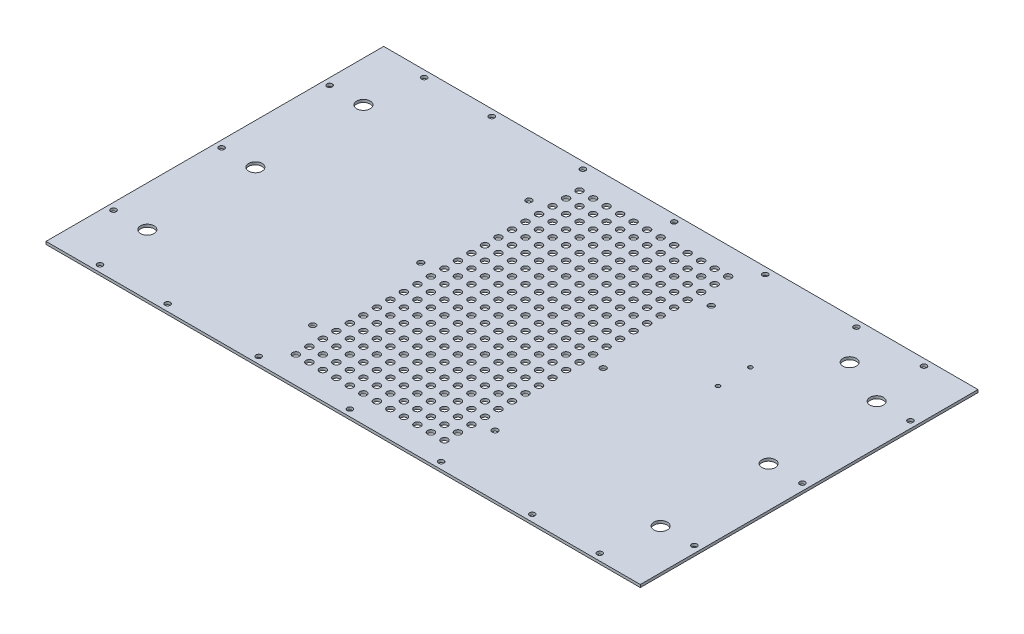
SolidWorks part; units mm, degrees
ref_plane "Alzado" through (0, 0, 0) normal (0, 0, 1) x (1, 0, 0)
ref_plane "Planta" through (0, 0, 0) normal (0, 1, 0) x (1, 0, 0)
ref_plane "Vista lateral" through (0, 0, 0) normal (1, 0, 0) x (0, 0, -1)
sketch "Croquis1" plane through (0, 0, 0) normal (0, 1, 0) x (1, 0, 0)
  line L8 (-100, 125) -> (-100, -125) construction
  line L9 (100, 125) -> (100, -125) construction
  line L13 (160, 125) -> (160, -125) construction
  line L16 (-220, 125) -> (-100, 125)
  line L17 (0, 125) -> (0, -125) construction
  line L20 (-100, 125) -> (100, 125)
  line L22 (-220, 0) -> (220, 0) construction
  line L24 (100, 125) -> (220, 125)
  line L26 (-60, 110) -> (-60, -110)
  line L28 (-220, -125) -> (-100, -125)
  line L31 (-100, -125) -> (100, -125)
  line L34 (100, -125) -> (220, -125)
  line L38 (-220, 125) -> (-220, -125)
  line L40 (-100, 125) -> (-100, -125)
  line L41 (100, 125) -> (100, -125)
  line L42 (-77.5, 102.5) -> (-77.5, 57.5) construction
  line L43 (220, 125) -> (220, -125)
  line L45 (-60, -110) -> (60, -110)
  line L46 (60, -110) -> (60, 110)
  line L47 (60, 110) -> (-60, 110)
  line L48 (-77.5, 57.5) -> (77.5, 57.5) construction
  line L49 (77.5, 57.5) -> (77.5, 102.5) construction
  line L50 (77.5, 102.5) -> (-77.5, 102.5) construction
  line L51 (-77.5, 22.5) -> (-77.5, -22.5) construction
  line L52 (-77.5, -22.5) -> (77.5, -22.5) construction
  line L53 (77.5, -22.5) -> (77.5, 22.5) construction
  line L54 (77.5, 22.5) -> (-77.5, 22.5) construction
  line L55 (-77.5, -57.5) -> (-77.5, -102.5) construction
  line L56 (-77.5, -102.5) -> (77.5, -102.5) construction
  line L57 (77.5, -102.5) -> (77.5, -57.5) construction
  line L58 (77.5, -57.5) -> (-77.5, -57.5) construction
  line L59 (-210, 115) -> (-210, -115) construction
  line L60 (-210, -115) -> (210, -115) construction
  line L61 (210, -115) -> (210, 115) construction
  line L62 (210, 115) -> (-210, 115) construction
  line L63 (-190, 125) -> (-190, -125) construction
  line L64 (190, 125) -> (190, -125) construction
  circle A0 centre (-190, 80) radius 5
  circle A1 centre (-190, 0) radius 5
  circle A2 centre (-190, -80) radius 5
  circle A3 centre (190, -80) radius 5
  circle A4 centre (190, 0) radius 5
  circle A5 centre (190, 80) radius 5
  circle A8 centre (-67.5, 80) radius 2.175
  circle A10 centre (-67.5, 0) radius 2.175
  circle A11 centre (-67.5, -80) radius 2.175
  circle A12 centre (67.5, -80) radius 2.175
  circle A13 centre (67.5, 0) radius 2.175
  circle A14 centre (67.5, 80) radius 2.175
  circle A15 centre (155, 95) radius 5
  point P8 (0, 125)
  point P44 (-220, 0)
  point P45 (-77.5, 80)
  point P46 (0, 102.5)
  point P47 (0, 110)
  dimension "D10" = 10
  dimension "D6" = 15
  dimension "D13" = 22.5
  dimension "D22" = 4.35
  dimension "D15" = 10
  dimension "D17" = 5
  dimension "D3" = 200
  dimension "D4" = 120
  dimension "D5" = 250
  dimension "D7" = 15
  dimension "D8" = 80
  dimension "D9" = 80
  dimension "D11" = 40
  dimension "D12" = 40
  dimension "D14" = 250
  dimension "D16" = 120
  dimension "D18" = 155
  dimension "D19" = 45
  dimension "D20" = 7.5
  dimension "D21" = 440
  dimension "D24" = 10
  dimension "D25" = 10
  dimension "D26" = 10
  dimension "D27" = 10
  dimension "D28" = 10
  dimension "D29" = 10
  dimension "D30" = 30
  dimension "D31" = 30
  dimension "D32" = 20
  dimension "D23" = 3
extrude "Saliente-Extruir1" add sketch "Croquis1" along normal blind 2 contours L40 L16 L38 L28 A2 A1 A0 | L41 L20 L40 L31 L47 L46 L45 L26 | L43 L24 L41 L34 A4 A3 A5
sketch "Croquis4" plane through (0, 2, 0) normal (0, 1, 0) x (1, 0, 0)
  line L0 (-60, 110) -> (-60, -110)
  line L1 (-60, -110) -> (60, -110)
  line L2 (60, -110) -> (60, 110)
  line L3 (60, 110) -> (-60, 110)
  circle A0 centre (-55, 105) radius 2.5
  circle A1 centre (-45, 105) radius 2.5
  circle A2 centre (-35, 105) radius 2.5
  circle A3 centre (-25, 105) radius 2.5
  circle A4 centre (-15, 105) radius 2.5
  circle A5 centre (-5, 105) radius 2.5
  circle A6 centre (5, 105) radius 2.5
  circle A7 centre (15, 105) radius 2.5
  circle A8 centre (25, 105) radius 2.5
  circle A9 centre (35, 105) radius 2.5
  circle A10 centre (45, 105) radius 2.5
  circle A12 centre (-45, 95) radius 2.5
  circle A13 centre (-35, 95) radius 2.5
  circle A14 centre (-25, 95) radius 2.5
  circle A15 centre (-15, 95) radius 2.5
  circle A16 centre (-5, 95) radius 2.5
  circle A17 centre (5, 95) radius 2.5
  circle A18 centre (15, 95) radius 2.5
  circle A19 centre (25, 95) radius 2.5
  circle A20 centre (35, 95) radius 2.5
  circle A21 centre (45, 95) radius 2.5
  circle A23 centre (-45, 85) radius 2.5
  circle A24 centre (-35, 85) radius 2.5
  circle A25 centre (-25, 85) radius 2.5
  circle A26 centre (-15, 85) radius 2.5
  circle A27 centre (-5, 85) radius 2.5
  circle A28 centre (5, 85) radius 2.5
  circle A29 centre (15, 85) radius 2.5
  circle A30 centre (25, 85) radius 2.5
  circle A31 centre (35, 85) radius 2.5
  circle A32 centre (45, 85) radius 2.5
  circle A34 centre (-45, 75) radius 2.5
  circle A35 centre (-35, 75) radius 2.5
  circle A36 centre (-25, 75) radius 2.5
  circle A37 centre (-15, 75) radius 2.5
  circle A38 centre (-5, 75) radius 2.5
  circle A39 centre (5, 75) radius 2.5
  circle A40 centre (15, 75) radius 2.5
  circle A41 centre (25, 75) radius 2.5
  circle A42 centre (35, 75) radius 2.5
  circle A43 centre (45, 75) radius 2.5
  circle A45 centre (-45, 65) radius 2.5
  circle A46 centre (-35, 65) radius 2.5
  circle A47 centre (-25, 65) radius 2.5
  circle A48 centre (-15, 65) radius 2.5
  circle A49 centre (-5, 65) radius 2.5
  circle A50 centre (5, 65) radius 2.5
  circle A51 centre (15, 65) radius 2.5
  circle A52 centre (25, 65) radius 2.5
  circle A53 centre (35, 65) radius 2.5
  circle A54 centre (45, 65) radius 2.5
  circle A56 centre (-45, 55) radius 2.5
  circle A57 centre (-35, 55) radius 2.5
  circle A58 centre (-25, 55) radius 2.5
  circle A59 centre (-15, 55) radius 2.5
  circle A60 centre (-5, 55) radius 2.5
  circle A61 centre (5, 55) radius 2.5
  circle A62 centre (15, 55) radius 2.5
  circle A63 centre (25, 55) radius 2.5
  circle A64 centre (35, 55) radius 2.5
  circle A65 centre (45, 55) radius 2.5
  circle A67 centre (-45, 45) radius 2.5
  circle A68 centre (-35, 45) radius 2.5
  circle A69 centre (-25, 45) radius 2.5
  circle A70 centre (-15, 45) radius 2.5
  circle A71 centre (-5, 45) radius 2.5
  circle A72 centre (5, 45) radius 2.5
  circle A73 centre (15, 45) radius 2.5
  circle A74 centre (25, 45) radius 2.5
  circle A75 centre (35, 45) radius 2.5
  circle A76 centre (45, 45) radius 2.5
  circle A78 centre (-45, 35) radius 2.5
  circle A79 centre (-35, 35) radius 2.5
  circle A80 centre (-25, 35) radius 2.5
  circle A81 centre (-15, 35) radius 2.5
  circle A82 centre (-5, 35) radius 2.5
  circle A83 centre (5, 35) radius 2.5
  circle A84 centre (15, 35) radius 2.5
  circle A85 centre (25, 35) radius 2.5
  circle A86 centre (35, 35) radius 2.5
  circle A87 centre (45, 35) radius 2.5
  circle A89 centre (-45, 25) radius 2.5
  circle A90 centre (-35, 25) radius 2.5
  circle A91 centre (-25, 25) radius 2.5
  circle A92 centre (-15, 25) radius 2.5
  circle A93 centre (-5, 25) radius 2.5
  circle A94 centre (5, 25) radius 2.5
  circle A95 centre (15, 25) radius 2.5
  circle A96 centre (25, 25) radius 2.5
  circle A97 centre (35, 25) radius 2.5
  circle A98 centre (45, 25) radius 2.5
  circle A100 centre (-45, 15) radius 2.5
  circle A101 centre (-35, 15) radius 2.5
  circle A102 centre (-25, 15) radius 2.5
  circle A103 centre (-15, 15) radius 2.5
  circle A104 centre (-5, 15) radius 2.5
  circle A105 centre (5, 15) radius 2.5
  circle A106 centre (15, 15) radius 2.5
  circle A107 centre (25, 15) radius 2.5
  circle A108 centre (35, 15) radius 2.5
  circle A109 centre (45, 15) radius 2.5
  circle A111 centre (-45, 5) radius 2.5
  circle A112 centre (-35, 5) radius 2.5
  circle A113 centre (-25, 5) radius 2.5
  circle A114 centre (-15, 5) radius 2.5
  circle A115 centre (-5, 5) radius 2.5
  circle A116 centre (5, 5) radius 2.5
  circle A117 centre (15, 5) radius 2.5
  circle A118 centre (25, 5) radius 2.5
  circle A119 centre (35, 5) radius 2.5
  circle A120 centre (45, 5) radius 2.5
  circle A122 centre (-45, -5) radius 2.5
  circle A123 centre (-35, -5) radius 2.5
  circle A124 centre (-25, -5) radius 2.5
  circle A125 centre (-15, -5) radius 2.5
  circle A126 centre (-5, -5) radius 2.5
  circle A127 centre (5, -5) radius 2.5
  circle A128 centre (15, -5) radius 2.5
  circle A129 centre (25, -5) radius 2.5
  circle A130 centre (35, -5) radius 2.5
  circle A131 centre (45, -5) radius 2.5
  circle A133 centre (-45, -15) radius 2.5
  circle A134 centre (-35, -15) radius 2.5
  circle A135 centre (-25, -15) radius 2.5
  circle A136 centre (-15, -15) radius 2.5
  circle A137 centre (-5, -15) radius 2.5
  circle A138 centre (5, -15) radius 2.5
  circle A139 centre (15, -15) radius 2.5
  circle A140 centre (25, -15) radius 2.5
  circle A141 centre (35, -15) radius 2.5
  circle A142 centre (45, -15) radius 2.5
  circle A144 centre (-45, -25) radius 2.5
  circle A145 centre (-35, -25) radius 2.5
  circle A146 centre (-25, -25) radius 2.5
  circle A147 centre (-15, -25) radius 2.5
  circle A148 centre (-5, -25) radius 2.5
  circle A149 centre (5, -25) radius 2.5
  circle A150 centre (15, -25) radius 2.5
  circle A151 centre (25, -25) radius 2.5
  circle A152 centre (35, -25) radius 2.5
  circle A153 centre (45, -25) radius 2.5
  circle A155 centre (-45, -35) radius 2.5
  circle A156 centre (-35, -35) radius 2.5
  circle A157 centre (-25, -35) radius 2.5
  circle A158 centre (-15, -35) radius 2.5
  circle A159 centre (-5, -35) radius 2.5
  circle A160 centre (5, -35) radius 2.5
  circle A161 centre (15, -35) radius 2.5
  circle A162 centre (25, -35) radius 2.5
  circle A163 centre (35, -35) radius 2.5
  circle A164 centre (45, -35) radius 2.5
  circle A166 centre (-45, -45) radius 2.5
  circle A167 centre (-35, -45) radius 2.5
  circle A168 centre (-25, -45) radius 2.5
  circle A169 centre (-15, -45) radius 2.5
  circle A170 centre (-5, -45) radius 2.5
  circle A171 centre (5, -45) radius 2.5
  circle A172 centre (15, -45) radius 2.5
  circle A173 centre (25, -45) radius 2.5
  circle A174 centre (35, -45) radius 2.5
  circle A175 centre (45, -45) radius 2.5
  circle A177 centre (-45, -55) radius 2.5
  circle A178 centre (-35, -55) radius 2.5
  circle A179 centre (-25, -55) radius 2.5
  circle A180 centre (-15, -55) radius 2.5
  circle A181 centre (-5, -55) radius 2.5
  circle A182 centre (5, -55) radius 2.5
  circle A183 centre (15, -55) radius 2.5
  circle A184 centre (25, -55) radius 2.5
  circle A185 centre (35, -55) radius 2.5
  circle A186 centre (45, -55) radius 2.5
  circle A188 centre (-45, -65) radius 2.5
  circle A189 centre (-35, -65) radius 2.5
  circle A190 centre (-25, -65) radius 2.5
  circle A191 centre (-15, -65) radius 2.5
  circle A192 centre (-5, -65) radius 2.5
  circle A193 centre (5, -65) radius 2.5
  circle A194 centre (15, -65) radius 2.5
  circle A195 centre (25, -65) radius 2.5
  circle A196 centre (35, -65) radius 2.5
  circle A197 centre (45, -65) radius 2.5
  circle A199 centre (-45, -75) radius 2.5
  circle A200 centre (-35, -75) radius 2.5
  circle A201 centre (-25, -75) radius 2.5
  circle A202 centre (-15, -75) radius 2.5
  circle A203 centre (-5, -75) radius 2.5
  circle A204 centre (5, -75) radius 2.5
  circle A205 centre (15, -75) radius 2.5
  circle A206 centre (25, -75) radius 2.5
  circle A207 centre (35, -75) radius 2.5
  circle A208 centre (45, -75) radius 2.5
  circle A210 centre (-45, -85) radius 2.5
  circle A211 centre (-35, -85) radius 2.5
  circle A212 centre (-25, -85) radius 2.5
  circle A213 centre (-15, -85) radius 2.5
  circle A214 centre (-5, -85) radius 2.5
  circle A215 centre (5, -85) radius 2.5
  circle A216 centre (15, -85) radius 2.5
  circle A217 centre (25, -85) radius 2.5
  circle A218 centre (35, -85) radius 2.5
  circle A219 centre (45, -85) radius 2.5
  circle A221 centre (-45, -95) radius 2.5
  circle A222 centre (-35, -95) radius 2.5
  circle A223 centre (-25, -95) radius 2.5
  circle A224 centre (-15, -95) radius 2.5
  circle A225 centre (-5, -95) radius 2.5
  circle A226 centre (5, -95) radius 2.5
  circle A227 centre (15, -95) radius 2.5
  circle A228 centre (25, -95) radius 2.5
  circle A229 centre (35, -95) radius 2.5
  circle A230 centre (45, -95) radius 2.5
  circle A232 centre (-55, 95) radius 2.5
  circle A233 centre (-55, 85) radius 2.5
  circle A234 centre (-55, 75) radius 2.5
  circle A235 centre (-55, 65) radius 2.5
  circle A236 centre (-55, 55) radius 2.5
  circle A237 centre (-55, 45) radius 2.5
  circle A238 centre (-55, 35) radius 2.5
  circle A239 centre (-55, 25) radius 2.5
  circle A240 centre (-55, 15) radius 2.5
  circle A241 centre (-55, 5) radius 2.5
  circle A242 centre (-55, -5) radius 2.5
  circle A243 centre (-55, -15) radius 2.5
  circle A244 centre (-55, -25) radius 2.5
  circle A245 centre (-55, -35) radius 2.5
  circle A246 centre (-55, -45) radius 2.5
  circle A247 centre (-55, -55) radius 2.5
  circle A248 centre (-55, -65) radius 2.5
  circle A249 centre (-55, -75) radius 2.5
  circle A250 centre (-55, -85) radius 2.5
  circle A251 centre (-55, -95) radius 2.5
  circle A252 centre (55, 105) radius 2.5
  circle A253 centre (55, 95) radius 2.5
  circle A254 centre (55, 85) radius 2.5
  circle A255 centre (55, 75) radius 2.5
  circle A256 centre (55, 65) radius 2.5
  circle A257 centre (55, 55) radius 2.5
  circle A258 centre (55, 45) radius 2.5
  circle A259 centre (55, 35) radius 2.5
  circle A260 centre (55, 25) radius 2.5
  circle A261 centre (55, 15) radius 2.5
  circle A262 centre (55, 5) radius 2.5
  circle A263 centre (55, -5) radius 2.5
  circle A264 centre (55, -15) radius 2.5
  circle A265 centre (55, -25) radius 2.5
  circle A266 centre (55, -35) radius 2.5
  circle A267 centre (55, -45) radius 2.5
  circle A268 centre (55, -55) radius 2.5
  circle A269 centre (55, -65) radius 2.5
  circle A270 centre (55, -75) radius 2.5
  circle A271 centre (55, -85) radius 2.5
  circle A272 centre (55, -95) radius 2.5
  circle A273 centre (-55, -105) radius 2.5
  circle A274 centre (-45, -105) radius 2.5
  circle A275 centre (-35, -105) radius 2.5
  circle A276 centre (-25, -105) radius 2.5
  circle A277 centre (-15, -105) radius 2.5
  circle A278 centre (-5, -105) radius 2.5
  circle A279 centre (5, -105) radius 2.5
  circle A280 centre (15, -105) radius 2.5
  circle A281 centre (25, -105) radius 2.5
  circle A282 centre (35, -105) radius 2.5
  circle A283 centre (45, -105) radius 2.5
  circle A284 centre (55, -105) radius 2.5
  dimension "D1" = 5
  dimension "D2" = 5
  dimension "D3" = 5
  dimension "D4" = 12
  dimension "D5" = 22
extrude "Saliente-Extruir4" add sketch "Croquis4" against normal blind 2
sketch "Croquis5" plane through (0, 2, 0) normal (0, 1, 0) x (1, 0, 0)
  line L0 (-210, 115) -> (-210, -115) construction
  line L1 (-210, 115) -> (210, 115) construction
  line L2 (210, 115) -> (210, -115) construction
  line L3 (210, -115) -> (-210, -115) construction
  line L4 (-220, 125) -> (-220, -125) construction
  line L5 (-220, 125) -> (220, 125) construction
  line L6 (-220, -125) -> (220, -125) construction
  line L7 (220, 125) -> (220, -125) construction
  line L8 (-100, 115) -> (-100, -115) construction
  line L9 (100, 115) -> (100, -115) construction
  line L10 (-220, 80) -> (220, 80) construction
  line L11 (-220, 0) -> (220, 0) construction
  line L12 (-220, -80) -> (220, -80) construction
  line L13 (-67.5, -115) -> (-67.5, 115) construction
  line L14 (67.5, -115) -> (67.5, 115) construction
  line L15 (-190, -125) -> (-190, 125) construction
  line L16 (190, -125) -> (190, 125) construction
  circle A0 centre (0, 120) radius 2
  circle A1 centre (0, -120) radius 2
  circle A2 centre (-215, 80) radius 2
  circle A3 centre (-215, 0) radius 2
  circle A4 centre (-215, -80) radius 2
  circle A5 centre (-67.5, -120) radius 2
  circle A6 centre (67.5, -120) radius 2
  circle A7 centre (-67.5, 120) radius 2
  circle A8 centre (215, 80) radius 2
  circle A9 centre (215, 0) radius 2
  circle A10 centre (215, -80) radius 2
  circle A11 centre (67.5, 120) radius 2
  circle A20 centre (-185, 120) radius 2
  circle A21 centre (-135, 120) radius 2
  circle A22 centre (-185, -120) radius 2
  circle A23 centre (-135, -120) radius 2
  circle A24 centre (135, 120) radius 2
  circle A25 centre (185, 120) radius 2
  circle A26 centre (135, -120) radius 2
  circle A27 centre (185, -120) radius 2
  dimension "D7" = 4
  dimension "D9" = 5
  dimension "D10" = 4
  dimension "D11" = 5
  dimension "D12" = 5
  dimension "D13" = 4
  dimension "D14" = 35
  dimension "D15" = 35
  dimension "D16" = 35
  dimension "D17" = 35
  dimension "D1" = 10
  dimension "D2" = 10
  dimension "D3" = 10
  dimension "D4" = 10
  dimension "D5" = 120
  dimension "D6" = 120
  dimension "D8" = 5
extrude "Cortar-Extruir1" cut sketch "Croquis5" against normal blind 10
sketch "Croquis6" plane through (0, 2, 0) normal (0, 1, 0) x (1, 0, 0)
  line L0 (-220, 125) -> (220, 125) construction
  line L1 (220, 125) -> (220, -125) construction
  circle A0 centre (121.5, 55) radius 1.5
  circle A1 centre (121.5, 31) radius 1.5
  dimension "D1" = 3
  dimension "D2" = 24
  dimension "D3" = 94
  dimension "D4" = 98.5
extrude "Cortar-Extruir2" cut sketch "Croquis6" against normal blind 10
